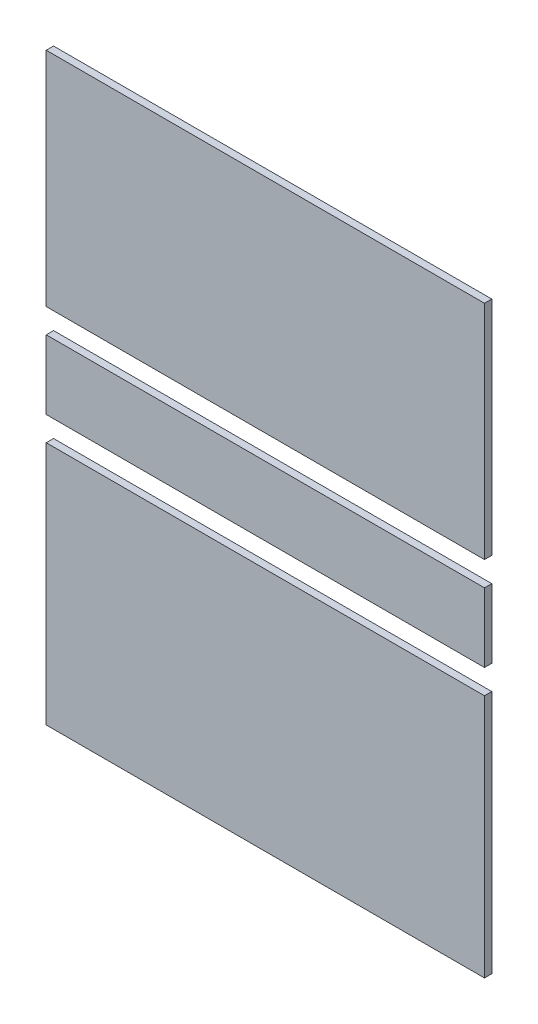
SolidWorks part; units mm, degrees
ref_plane "Front Plane" through (0, 0, 0) normal (0, 0, 1) x (1, 0, 0)
ref_plane "Top Plane" through (0, 0, 0) normal (0, 1, 0) x (1, 0, 0)
ref_plane "Right Plane" through (0, 0, 0) normal (1, 0, 0) x (0, 0, -1)
sketch "Sketch1" plane through (0, 0, 0) normal (0, 0, 1) x (1, 0, 0)
  line L1 (0, 0) -> (304.8, 0)
  line L2 (0, 0) -> (0, 406.4)
  line L3 (0, 406.4) -> (304.8, 406.4)
  line L4 (304.8, 0) -> (304.8, 406.4)
  line L5 (0, 252) -> (304.8, 252)
  line L6 (0, 252) -> (0, 170)
  line L7 (0, 170) -> (304.8, 170)
  line L8 (304.8, 252) -> (304.8, 170)
  dimension "D1" = 406.4
  dimension "D2" = 304.8
  dimension "D3" = 170
  dimension "D4" = 82
extrude "Boss-Extrude1" add sketch "Sketch1" along normal blind 5.08 contours L2 L5 L4 L3 | L7 L2 L1 L4
sketch "Sketch2" plane through (0, 0, 5.08) normal (0, 0, 1) x (1, 0, 0)
  line L0 (304.8, 252) -> (304.8, 406.4) construction
  line L1 (0, 235) -> (304.8, 235)
  line L2 (0, 235) -> (0, 187)
  line L3 (0, 187) -> (304.8, 187)
  line L4 (304.8, 235) -> (304.8, 187)
  line L5 (0, 252) -> (0, 406.4) construction
  line L6 (0, 252) -> (304.8, 252) construction
  line L7 (0, 170) -> (304.8, 170) construction
  dimension "D1" = 17
  dimension "D2" = 17
extrude "Boss-Extrude2" add sketch "Sketch2" against normal up to surface (5.08 mm away) separate body up to face at (152.4, 329.2, 0)
